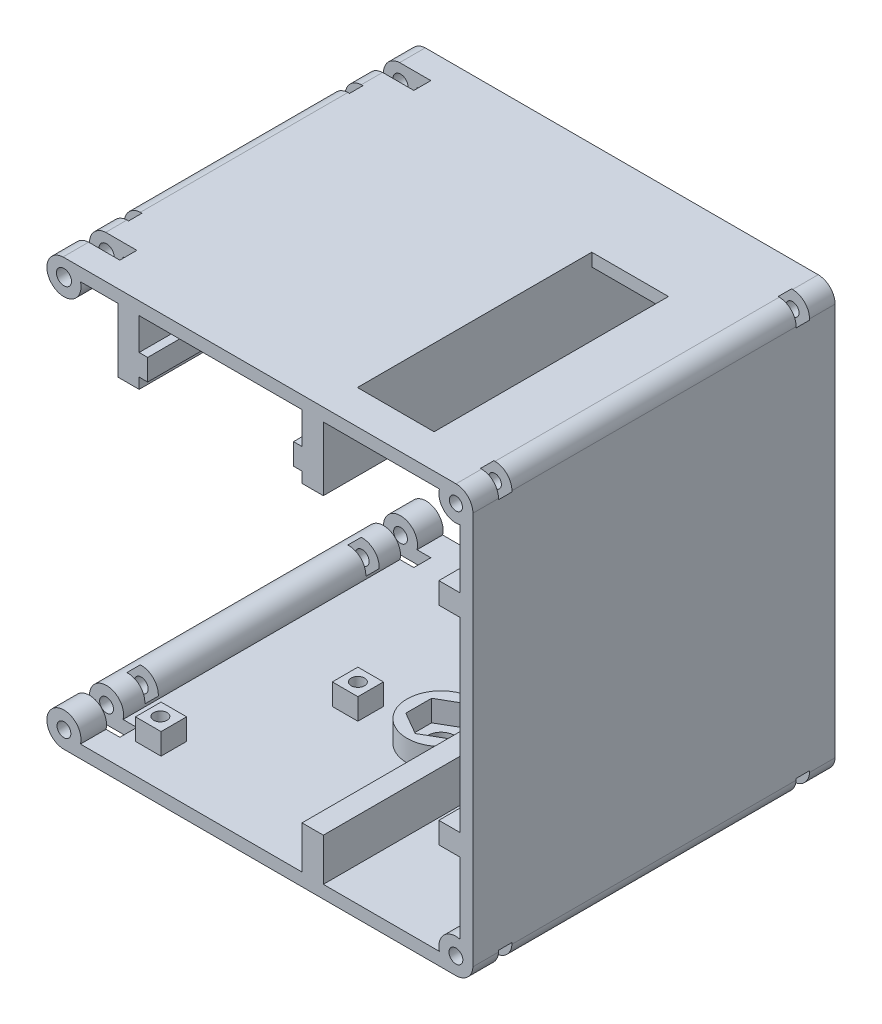
SolidWorks part; units mm, degrees
ref_plane "Ön Düzlem" through (0, 0, 0) normal (0, 0, 1) x (1, 0, 0)
ref_plane "Üst Düzlem" through (0, 0, 0) normal (0, 1, 0) x (1, 0, 0)
ref_plane "Sağ Düzlem" through (0, 0, 0) normal (1, 0, 0) x (0, 0, -1)
sketch "Çizim1" plane through (0, 0, 0) normal (0, 0, 1) x (1, 0, 0)
  line L0 (-44.4053, 60.3927) -> (39.8513, 60.3927)
  line L1 (-48.4826, 63.3927) -> (43.7508, 63.3927)
  line L2 (-52.2796, 59.3978) -> (-52.2796, -32.6022)
  line L3 (-49.2796, -33.5872) -> (44.7153, -33.6022) construction
  line L4 (47.7153, 59.3978) -> (47.7153, -32.8029)
  line L5 (44.7153, 60.5619) -> (44.7153, 60.3927)
  line L6 (-44.403, -33.588) -> (39.8472, -33.6014)
  line L7 (-49.2796, 55.5248) -> (-49.2796, -28.7292)
  line L8 (-52.2796, -36.5867) -> (47.7153, -36.6027) construction
  line L9 (-47.9365, -36.5874) -> (43.7544, -36.602)
  line L10 (-52.2796, 63.3927) -> (-52.2796, -36.5867) construction
  line L11 (-49.2796, 60.3927) -> (-49.2796, -33.5872) construction
  line L12 (47.7153, 63.3927) -> (47.7153, -36.6027) construction
  line L13 (44.7153, 60.3927) -> (44.7153, -33.6022) construction
  line L14 (-49.2796, 60.3927) -> (44.7153, 60.3927) construction
  line L15 (-52.2796, 63.3927) -> (47.7153, 63.3927) construction
  line L16 (-52.2796, -32.6022) -> (-52.2796, 59.3978) construction
  line L17 (44.7153, 55.5287) -> (44.7153, -28.7279)
  line L18 (44.7153, 60.3927) -> (44.8846, 60.3927)
  arc A0 (-48.4826, 63.3927) -> (-52.2796, 59.3978) centre (-48.2796, 59.3978) ccw
  arc A1 (47.7153, 59.3978) -> (43.7508, 63.3927) centre (43.7204, 59.3978) ccw
  arc A2 (43.7544, -36.602) -> (47.7153, -32.8029) centre (43.7204, -32.6022) ccw
  arc A3 (-52.2796, -32.6022) -> (-47.9365, -36.5874) centre (-48.2796, -32.6022) ccw
  arc A4 (-44.403, -33.588) -> (-49.2796, -28.7292) centre (-48.2796, -32.6022) ccw
  arc A5 (44.7153, -28.7279) -> (39.8472, -33.6014) centre (43.7204, -32.6022) ccw
  arc A6 (47.5895, 60.3927) -> (44.7153, 63.2669) centre (43.7204, 59.3978) ccw
  arc A7 (-49.2796, 55.5248) -> (-44.4053, 60.3927) centre (-48.2796, 59.3978) ccw
  circle A8 centre (-48.2796, 59.3978) radius 1.7694
  circle A9 centre (43.7204, 59.3978) radius 1.5314
  circle A10 centre (43.7204, -32.6022) radius 1.625
  circle A11 centre (-48.2796, -32.6022) radius 1.625
  arc A12 (-52.2796, -32.6022) -> (-48.2796, -36.6022) centre (-48.2796, -32.6022) ccw construction
  arc A13 (39.8513, 60.3927) -> (43.6899, 63.3927) centre (43.7204, 59.3978) ccw
  arc A14 (43.7204, -36.6022) -> (47.7204, -32.6022) centre (43.7204, -32.6022) ccw construction
  circle A15 centre (-48.2796, 59.3978) radius 1.625 construction
  arc A16 (-48.2796, 63.3978) -> (-52.2796, 59.3978) centre (-48.2796, 59.3978) ccw construction
  dimension "D2" = 3
  dimension "D1" = 3
extrude "Yükseklik-Ekstrüzyon1" add sketch "Çizim1" along normal blind 85
ref_plane "Düzlem1" through (5.5565, 5.5565, 0) normal (0.7071, 0.7071, 0) x (0.7071, -0.7071, 0)
ref_plane "Düzlem2" through (-7.8423, 7.8435, 0) normal (0.7071, -0.7072, 0) x (0, 0, 1)
sketch "Çizim3" plane through (5.5565, 5.5565, 0) normal (0.7071, 0.7071, 0) x (0.7071, -0.7071, 0)
  line L0 (-8.2608, 0) -> (-13.8889, 0) construction
  line L2 (-14.0748, -9.15) -> (-8.0748, -9.15)
  line L3 (-14.0748, -9.15) -> (-14.0748, -6)
  line L4 (-14.0748, -6) -> (-8.0748, -6)
  line L6 (-8.0748, -9.15) -> (-8.0748, -6)
  line L7 (-14.0748, -9.15) -> (-8.0748, -6) construction
  line L8 (-14.0748, -6) -> (-8.0748, -9.15) construction
  point P0 (-11.0748, -7.575)
  point P7 (-11.0748, 0)
  dimension "D1" = 6
  dimension "D2" = 3.15
  dimension "D3" = 6
extrude "Kes-Ekstrüzyon2" cut sketch "Çizim3" along normal blind 94
ref_plane "Düzlem3" through (-2.2822, 0, 0) normal (-1, 0, 0) x (0, 0, 1)
mirror "Aynalama1" about plane through (-2.2822, 0, 0) normal (-1, 0, 0) of "Kes-Ekstrüzyon2"
sketch "Çizim4" plane through (-7.8423, 7.8435, 0) normal (0.7071, -0.7072, 0) x (0, 0, 1)
  line L1 (6, -10.8056) -> (9.15, -10.8056)
  line L2 (6, -10.8056) -> (6, -4.8056)
  line L3 (6, -4.8056) -> (9.15, -4.8056)
  line L4 (9.15, -10.8056) -> (9.15, -4.8056)
  line L5 (6, -10.8056) -> (9.15, -4.8056) construction
  line L6 (6, -4.8056) -> (9.15, -10.8056) construction
  line L7 (0, -5.062) -> (0, -10.5492) construction
  point P0 (7.575, -7.8056)
  point P8 (0, -7.8056)
  dimension "D1" = 3.15
  dimension "D2" = 6
  dimension "D3" = 3
extrude "Kes-Ekstrüzyon3" cut sketch "Çizim4" along normal blind 91
mirror "Aynalama2" about plane through (-2.2822, 0, 0) normal (-1, 0, 0) of "Kes-Ekstrüzyon3"
ref_plane "Düzlem4" through (0, 0, 42.5) normal (0, 0, -1) x (-1, 0, 0)
mirror "Aynalama3" about plane through (0, 0, 42.5) normal (0, 0, -1) of "Aynalama2", "Aynalama1", "Kes-Ekstrüzyon2", "Kes-Ekstrüzyon3"
sketch "Çizim5" plane through (-0.0053, -33.5951, 0) normal (0.0002, 1, 0) x (1, -0.0002, 0)
  line L1 (-2.2568, -36.4378) -> (-7.5068, -39.4689)
  line L2 (-7.5068, -39.4689) -> (-7.5068, -45.5311)
  line L3 (-7.5068, -45.5311) -> (-2.2568, -48.5622)
  line L4 (-2.2568, -48.5622) -> (2.9932, -45.5311)
  line L5 (2.9932, -45.5311) -> (2.9932, -39.4689)
  line L6 (2.9932, -39.4689) -> (-2.2568, -36.4378)
  circle A0 centre (-2.2568, -42.5) radius 5.25 construction
  circle A1 centre (-2.2568, -42.5) radius 8
  dimension "D2" = 16
  dimension "D1" = 10.5
extrude "Yükseklik-Ekstrüzyon2" add sketch "Çizim5" along normal blind 5
sketch "Çizim6" plane through (-0.0058, -36.5951, 0) normal (-0.0002, -1, 0) x (1, -0.0002, 0)
  circle A0 centre (-2.2568, 42.5) radius 3.1737
  dimension "D1" = 6.3474
extrude "Kes-Ekstrüzyon4" cut sketch "Çizim6" against normal blind 6
sketch "Çizim7" plane through (0, 0, 85) normal (0, 0, 1) x (1, 0, 0)
  line L0 (44.7153, 55.5287) -> (44.7153, -28.7279) construction
  line L1 (44.7153, 41.7036) -> (39.7153, 41.7036)
  line L2 (44.7153, 41.7036) -> (44.7153, 36.7036)
  line L3 (44.7153, 36.7036) -> (39.7153, 36.7036)
  line L4 (39.7153, 41.7036) -> (39.7153, 36.7036)
  line L5 (-44.403, -33.588) -> (39.8472, -33.6014) construction
  line L6 (44.7153, -7.0212) -> (39.7153, -7.0212)
  line L7 (44.7153, -7.0212) -> (44.7153, -12.0212)
  line L8 (44.7153, -12.0212) -> (39.7153, -12.0212)
  line L9 (39.7153, -7.0212) -> (39.7153, -12.0212)
  line L10 (12.6035, -33.5971) -> (7.6035, -33.5971)
  line L11 (12.6035, -33.5971) -> (12.6035, -23.5971)
  line L12 (12.6035, -23.5971) -> (7.6035, -23.5971)
  line L13 (7.6035, -33.5971) -> (7.6035, -23.5971)
  line L14 (-44.4053, 60.3927) -> (39.8513, 60.3927) construction
  line L15 (12.6035, 60.3927) -> (7.6035, 60.3927)
  line L16 (12.6035, 60.3927) -> (12.6035, 45.3927)
  line L17 (12.6035, 45.3927) -> (7.6035, 45.3927)
  line L18 (7.6035, 60.3927) -> (7.6035, 45.3927)
  dimension "D1" = 5
  dimension "D2" = 5
  dimension "D3" = 5
  dimension "D4" = 5
  dimension "D5" = 5
  dimension "D6" = 10
  dimension "D7" = 15
  dimension "D8" = 5
extrude "Yükseklik-Ekstrüzyon3" add sketch "Çizim7" against normal up to surface (85 mm away) up to face at (-2.2674, 13.3525, 0)
sketch "Çizim8" plane through (0, 63.3927, 0) normal (0, 1, 0) x (1, 0, 0)
  line L0 (12.6035, 0) -> (12.6035, -85) construction
  line L1 (12.6035, -22) -> (30.6035, -22)
  line L2 (12.6035, -22) -> (12.6035, -77)
  line L3 (12.6035, -77) -> (30.6035, -77)
  line L4 (30.6035, -22) -> (30.6035, -77)
  line L5 (-48.4826, -85) -> (43.7508, -85) construction
  dimension "D1" = 18
  dimension "D2" = 55
  dimension "D3" = 8
extrude "Kes-Ekstrüzyon5" cut sketch "Çizim8" against normal blind 3
sketch "Çizim9" plane through (0, 0, 85) normal (0, 0, 1) x (1, 0, 0)
  line L0 (7.6035, 60.3927) -> (7.6035, 45.3927) construction
  line L1 (7.6035, 52.8927) -> (5.6035, 52.8927)
  line L2 (7.6035, 52.8927) -> (7.6035, 47.8927)
  line L3 (7.6035, 47.8927) -> (5.6035, 47.8927)
  line L4 (5.6035, 52.8927) -> (5.6035, 47.8927)
  line L5 (-44.4053, 60.3927) -> (7.6035, 60.3927) construction
  line L6 (-35.6305, 60.3927) -> (-30.6305, 60.3927)
  line L7 (-35.6305, 60.3927) -> (-35.6305, 45.3927)
  line L8 (-35.6305, 45.3927) -> (-30.6305, 45.3927)
  line L9 (-30.6305, 60.3927) -> (-30.6305, 45.3927)
  line L11 (-30.6305, 47.8927) -> (-28.6305, 47.8927)
  line L12 (-30.6305, 47.8927) -> (-30.6305, 52.8927)
  line L13 (-30.6305, 52.8927) -> (-28.6305, 52.8927)
  line L14 (-28.6305, 47.8927) -> (-28.6305, 52.8927)
  line M14 (-44.4053, 60.3927) -> (7.6035, 60.3927)
  line M15 (7.6035, 60.3927) -> (7.6035, 45.3927)
  dimension "D1" = 2
  dimension "D2" = 5
  dimension "D3" = 5
  dimension "D4" = 2
  dimension "D5" = 5
extrude "Yükseklik-Ekstrüzyon4" add sketch "Çizim9" against normal up to surface (85 mm away) contours L11 L14 L13 L9 | L9 L7 L8 M14 | L1 L4 L3 M15 up to face at (16.6795, 13.4627, 0)
sketch "Çizim10" plane through (-0.0053, -33.5951, 0) normal (0.0002, 1, 0) x (1, -0.0002, 0)
  line L1 (-22.485, -47.8) -> (-16.485, -47.8)
  line L2 (-22.485, -47.8) -> (-22.485, -41.8)
  line L3 (-22.485, -41.8) -> (-16.485, -41.8)
  line L4 (-16.485, -47.8) -> (-16.485, -41.8)
  line L5 (-22.485, -47.8) -> (-16.485, -41.8) construction
  line L6 (-22.485, -41.8) -> (-16.485, -47.8) construction
  line L7 (-38.485, -78) -> (-32.485, -78)
  line L8 (-38.485, -78) -> (-38.485, -72)
  line L9 (-38.485, -72) -> (-32.485, -72)
  line L10 (-32.485, -78) -> (-32.485, -72)
  line L11 (-38.485, -78) -> (-32.485, -72) construction
  line L12 (-38.485, -72) -> (-32.485, -78) construction
  line L14 (-44.3977, -85) -> (7.6089, -85) construction
  point P0 (-19.485, -44.8)
  point P5 (-35.485, -75)
  dimension "D1" = 6
  dimension "D2" = 6
  dimension "D3" = 6
  dimension "D4" = 6
  dimension "D5" = 30.2
  dimension "D6" = 16
  dimension "D7" = 10
extrude "Yükseklik-Ekstrüzyon5" add sketch "Çizim10" along normal blind 5
sketch "Çizim12" plane through (-0.0046, -28.5951, 0) normal (0.0002, 1, 0) x (1, -0.0002, 0)
  line L0 (-35.6401, 0) -> (-35.6401, -85) construction
  circle A0 centre (-35.6401, -75) radius 1.575
  circle A1 centre (-19.485, -44.8) radius 1.575
  dimension "D1" = 3.15
  dimension "D2" = 3.15
extrude "Kes-Ekstrüzyon6" cut sketch "Çizim12" against normal blind 5
sketch "Çizim13" plane through (0, 0, 85) normal (0, 0, 1) x (1, 0, 0)
  line L0 (-52.2796, 59.3978) -> (-52.2796, -32.6022) construction
  line L1 (-49.2796, 55.5248) -> (-52.2796, 55.5248)
  line L2 (-49.2796, 55.5248) -> (-49.2796, -28.7292)
  line L3 (-49.2796, -28.7292) -> (-52.2796, -28.7292)
  line L4 (-52.2796, 55.5248) -> (-52.2796, -28.7292)
extrude "Kes-Ekstrüzyon7" cut sketch "Çizim13" against normal through all
sketch "Çizim14" plane through (-52.2796, 0, 0) normal (-1, 0, 0) x (0, 0, 1)
  line L1 (6, 63.3927) -> (10, 63.3927)
  line L2 (6, 63.3927) -> (6, 53.3927)
  line L3 (6, 53.3927) -> (10, 53.3927)
  line L4 (10, 63.3927) -> (10, 53.3927)
  line L5 (75, 63.3927) -> (79, 63.3927)
  line L6 (75, 63.3927) -> (75, 53.7711)
  line L7 (75, 53.7711) -> (79, 53.7711)
  line L8 (79, 63.3927) -> (79, 53.7711)
  line L9 (85, 59.3978) -> (85, 63.3927) construction
  dimension "D1" = 4
  dimension "D2" = 6
  dimension "D3" = 4
  dimension "D4" = 10
extrude "Kes-Ekstrüzyon8" cut sketch "Çizim14" against normal blind 11.1211
sketch "Çizim15" plane through (0, 63.3927, 0) normal (0, 1, 0) x (1, 0, 0)
  line L0 (-41.1585, -75) -> (-48.4826, -75) construction
  line L1 (-41.1585, -6) -> (-52.2796, -6)
  line L2 (-41.1585, -6) -> (-41.1585, -10)
  line L3 (-41.1585, -10) -> (-52.2796, -10)
  line L4 (-52.2796, -6) -> (-52.2796, -10)
  line L5 (-41.1585, -75) -> (-52.2796, -75)
  line L6 (-41.1585, -75) -> (-41.1585, -79)
  line L7 (-41.1585, -79) -> (-52.2796, -79)
  line L8 (-52.2796, -75) -> (-52.2796, -79)
  line L9 (-41.1585, -79) -> (-41.1585, -75) construction
  line L10 (-48.4826, -79) -> (-52.2796, -79) construction
  line L11 (-52.2796, -85) -> (-52.2796, -79) construction
extrude "Kes-Ekstrüzyon9" cut sketch "Çizim15" against normal through all
sketch "Çizim16" plane through (0, 0, 85) normal (0, 0, 1) x (1, 0, 0)
  line L1 (-48.2796, -32.6022) -> (-52.2796, -32.6022)
  line L2 (-48.2796, -32.6022) -> (-48.2796, -28.7292)
  line L3 (-48.2796, -28.7292) -> (-52.2796, -28.7292)
  line L4 (-52.2796, -32.6022) -> (-52.2796, -28.7292)
  circle A0 centre (-48.2796, -32.6022) radius 4
  line M1 (-49.2796, -28.7292) -> (-52.2796, -28.7292)
  line M2 (-52.2796, -28.7292) -> (-52.2796, -32.6022)
extrude "Kes-Ekstrüzyon10" cut sketch "Çizim16" against normal through all contours A0 M1 M2
sketch "Çizim19" plane through (0, 0, 85) normal (0, 0, 1) x (1, 0, 0)
  line L0 (-52.2796, -32.6022) -> (-52.2796, 59.3978) construction
  line L1 (-48.2796, 59.3978) -> (-52.2796, 59.3978)
  line L2 (-48.2796, 59.3978) -> (-48.2796, 55.5248)
  line L3 (-48.2796, 55.5248) -> (-52.2796, 55.5248)
  line L4 (-52.2796, 59.3978) -> (-52.2796, 55.5248)
  line L5 (-49.2796, 55.5248) -> (-52.2796, 55.5248) construction
  circle A0 centre (-48.2796, 59.3978) radius 4
  line M13 (-52.2796, 59.3978) -> (-52.2796, 55.5248)
  line M14 (-52.2796, 55.5248) -> (-49.2796, 55.5248)
extrude "Kes-Ekstrüzyon12" cut sketch "Çizim19" against normal through all contours A0 M13 M14
sketch "Çizim18" plane through (-7.8423, 7.8435, 0) normal (0.7071, -0.7072, 0) x (0, 0, 1)
  line L1 (15, -4.8056) -> (18.15, -4.8056)
  line L2 (15, -4.8056) -> (15, -10.8056)
  line L3 (15, -10.8056) -> (18.15, -10.8056)
  line L4 (18.15, -4.8056) -> (18.15, -10.8056)
  line L5 (0, -5.062) -> (0, -10.5492) construction
  line L6 (42.5, -5.062) -> (42.5, -25.4028) construction
  line L7 (75.85, -5.062) -> (9.15, -5.062) construction
  line L8 (66.85, -4.8056) -> (66.85, -10.8056)
  line L9 (70, -10.8056) -> (66.85, -10.8056)
  line L10 (70, -4.8056) -> (70, -10.8056)
  line L11 (70, -4.8056) -> (66.85, -4.8056)
  point P6 (0, -7.8056)
  point P7 (15, -7.8056)
  dimension "D1" = 6
  dimension "D2" = 3.15
  dimension "D3" = 15
extrude "Kes-Ekstrüzyon13" cut sketch "Çizim18" against normal blind 30 from offset 55 offset against normal yes
sketch "Çizim20" plane through (5.5565, 5.5565, 0) normal (0.7071, 0.7071, 0) x (0.7071, -0.7071, 0)
  line L0 (-80.1395, -15) -> (-78.7276, -15) construction
  line L1 (-14.0748, -15) -> (-8.0748, -15)
  line L2 (-14.0748, -15) -> (-14.0748, -18.15)
  line L3 (-14.0748, -18.15) -> (-8.0748, -18.15)
  line L4 (-8.0748, -15) -> (-8.0748, -18.15)
  line L5 (-8.2608, -9.15) -> (-13.8889, -9.15) construction
  line L6 (-13.8889, -42.5) -> (-70.0632, -42.5) construction
  line L7 (-13.8889, -75.85) -> (-13.8889, -9.15) construction
  line L8 (-8.0748, -70) -> (-8.0748, -66.85)
  line L9 (-14.0748, -66.85) -> (-8.0748, -66.85)
  line L10 (-14.0748, -70) -> (-14.0748, -66.85)
  line L11 (-14.0748, -70) -> (-8.0748, -70)
  point P6 (-11.0748, -15)
  point P9 (-11.0748, -9.15)
  dimension "D1" = 3.15
  dimension "D2" = 6
extrude "Kes-Ekstrüzyon14" cut sketch "Çizim20" against normal blind 30 from offset 55
